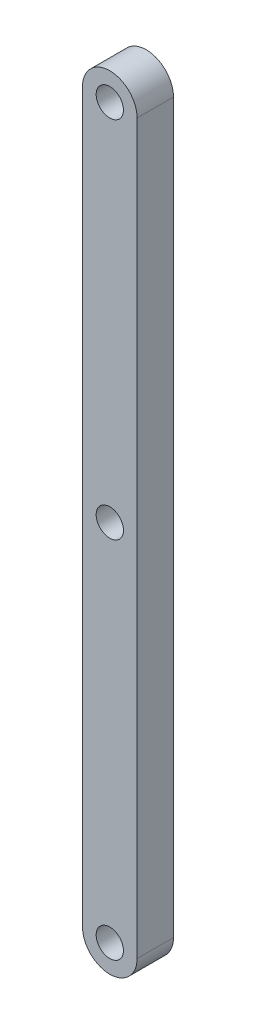
SolidWorks part; units mm, degrees
ref_plane "Alzado" through (0, 0, 0) normal (0, 0, 1) x (1, 0, 0)
ref_plane "Planta" through (0, 0, 0) normal (0, 1, 0) x (1, 0, 0)
ref_plane "Vista lateral" through (0, 0, 0) normal (1, 0, 0) x (0, 0, -1)
sketch "Croquis1" plane through (0, 0, 0) normal (0, 0, 1) x (1, 0, 0)
  line L0 (0, 0) -> (0, 400) construction
  line L1 (-15, 0) -> (-15, 400)
  line L2 (15, 0) -> (15, 400)
  arc A0 (-15, 0) -> (15, 0) centre (0, 0) ccw
  arc A1 (15, 400) -> (-15, 400) centre (0, 400) ccw
  circle A2 centre (0, 400) radius 7.5
  circle A3 centre (0, 200) radius 7.5
  circle A4 centre (0, 0) radius 7.5
  point P3 (0, 200)
  point P14 (0, 300)
  point P15 (129.0328, 270.833)
  point P16 (0, 0)
  dimension "D3" = 15
  dimension "D1" = 400
  dimension "D2" = 30
extrude "Saliente-Extruir1" add sketch "Croquis1" along normal blind 20
